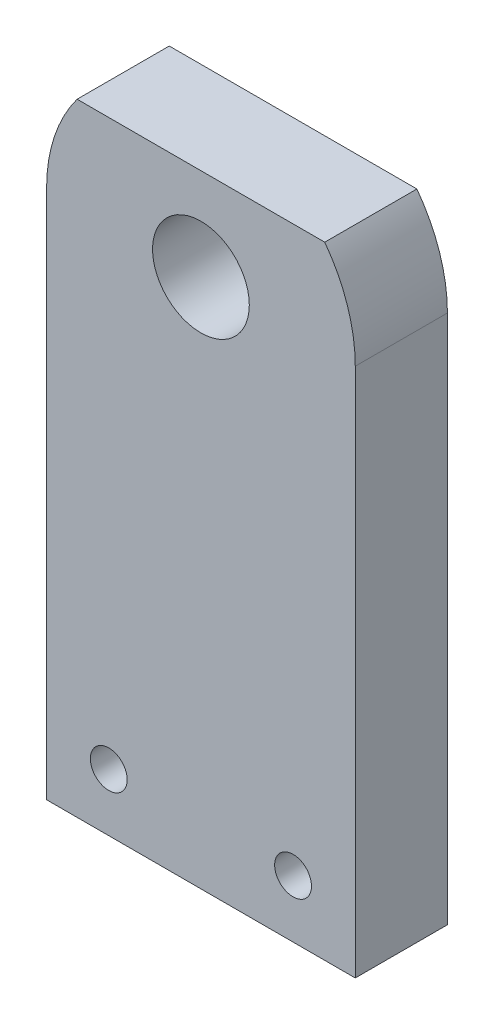
SolidWorks part; units mm, degrees
material "Liga 1060"
ref_plane "Plano frontal" through (0, 0, 0) normal (0, 0, 1) x (1, 0, 0)
ref_plane "Plano superior" through (0, 0, 0) normal (0, 1, 0) x (1, 0, 0)
ref_plane "Plano direito" through (0, 0, 0) normal (1, 0, 0) x (0, 0, -1)
sketch "Esboço1" plane through (0, 0, 0) normal (0, 0, 1) x (1, 0, 0)
  line L0 (-6.7, 0) -> (-6.7, -23)
  line L1 (6.7, 0) -> (6.7, -23)
  line L2 (6.7, -23) -> (-6.7, -23)
  line L3 (-5.3749, 4) -> (5.3749, 4)
  arc A0 (6.7, 0) -> (5.3749, 4) centre (0, 0) ccw
  arc A1 (-5.3749, 4) -> (-6.7, 0) centre (0, 0) ccw
  dimension "D1" = 13.4
  dimension "D2" = 23
  dimension "D3" = 4
extrude "Ressalto-extrusão1" add sketch "Esboço1" along normal blind 4
sketch "Esboço2" plane through (0, 0, 4) normal (0, 0, 1) x (1, 0, 0)
  circle A0 centre (0, 0) radius 3 construction
  point P3 (0, 3)
  point P11 (0, 0)
  dimension "D1" = 6
sketch "Esboço4" plane through (0, 0, 4) normal (0, 0, 1) x (1, 0, 0)
  line L0 (0, -23) -> (0, -20.5) construction
  line L1 (-6.7, -23) -> (6.7, -23) construction
  line L2 (-4, -20.5) -> (4, -20.5) construction
  dimension "D1" = 2.5
  dimension "D2" = 8
hole_wizard "Furo roscado de M2x0.41" positions "3DSketch3" profile "Esboço5" tap size "M2x0.4" standard "Ansi Metric" end condition through all
sketch3d "3DSketch3"
  point P0 (-4, -20.5, 4)
  point P6 (4, -20.5, 4)
sketch "Esboço5" plane through (-4, -20.5, 4) normal (1, 0, 0) x (0, -1, 0)
  line L0 (0, 0) -> (0, 4)
  line L1 (0, 4) -> (0.8, 4)
  line L2 (0.8, 4) -> (0.8, 0)
  line L5 (0.8, 0) -> (0, 0)
  line L11 (0, -6.35) -> (0, 107.95) construction
  dimension "Thru Tap Drill Dia." = 1.6
  dimension "Thru Tap Drill Depth" = 4
cosmetic thread "Rosca de furo1" parameters "D2"=2
cosmetic thread "Rosca de furo3" parameters "D2"=2
hole_wizard "Furo roscado para conduíte de M4x0.71" positions "Esboço6" profile "Esboço8" tap size "M4x0.7" standard "Helicoil® Metric" end condition through all
sketch "Esboço6" plane through (0, 0, 4) normal (0, 0, 1) x (1, 0, 0)
  point P0 (0, 0)
sketch "Esboço8" plane through (0, 0, 4) normal (1, 0, 0) x (0, -1, 0)
  line L0 (0, 0) -> (0, 4)
  line L1 (0, 4) -> (2.1, 4)
  line L2 (2.1, 4) -> (2.1, 0)
  line L5 (2.1, 0) -> (0, 0)
  line L11 (0, -6.35) -> (0, 107.95) construction
  dimension "Thru Tap Drill Dia." = 4.2
  dimension "Thru Tap Drill Depth" = 4
cosmetic thread "Rosca de furo4" parameters "D1"=4.7, "D2"=5.007
